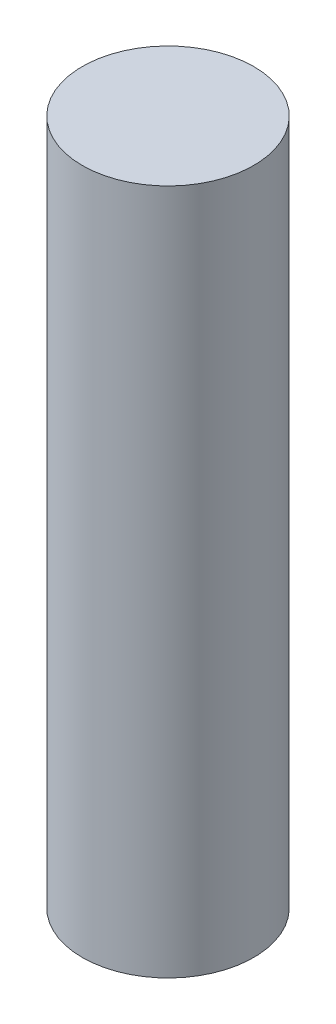
SolidWorks part; units mm, degrees
material "Miedź"
ref_plane "Front Plane" through (0, 0, 0) normal (0, 0, 1) x (1, 0, 0)
ref_plane "Top Plane" through (0, 0, 0) normal (0, 1, 0) x (1, 0, 0)
ref_plane "Right Plane" through (0, 0, 0) normal (1, 0, 0) x (0, 0, -1)
sketch "Szkic1" plane through (0, 0, 0) normal (0, 1, 0) x (1, 0, 0)
  circle A0 centre (0, 0) radius 0.25
extrude "Dodanie-wyciągnięcie1" add sketch "Szkic1" along normal blind 2
